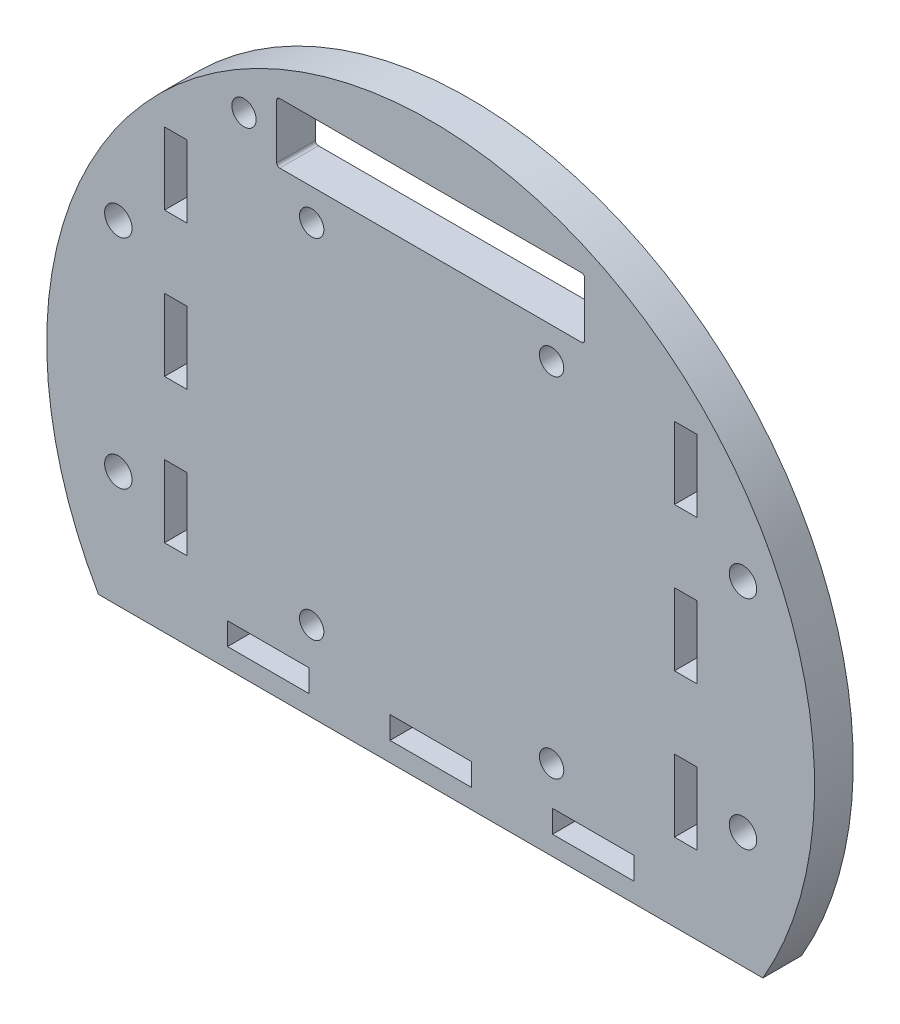
SolidWorks part; units mm, degrees
material "ABS"
ref_plane "Front Plane" through (0, 0, 0) normal (0, 0, 1) x (1, 0, 0)
ref_plane "Top Plane" through (0, 0, 0) normal (0, 1, 0) x (1, 0, 0)
ref_plane "Right Plane" through (0, 0, 0) normal (1, 0, 0) x (0, 0, -1)
sketch "Sketch1" plane through (0, 0, 0) normal (0, 0, 1) x (1, 0, 0)
  line L0 (-54.5148, -31.5775) -> (54.5148, -31.5775) construction
  line L1 (-54.5148, -31.5775) -> (54.5148, -31.5775)
  line L4 (20, -28.4025) -> (33.3333, -28.4025)
  line L5 (20, -24.7275) -> (20, -28.4025)
  line L6 (33.3333, -24.7275) -> (20, -24.7275)
  line L7 (33.3333, -28.4025) -> (33.3333, -24.7275)
  line L8 (20, -28.4025) -> (33.3333, -28.4025)
  line L9 (20, -24.7275) -> (20, -28.4025)
  line L10 (33.3333, -24.7275) -> (20, -24.7275)
  line L11 (33.3333, -28.4025) -> (33.3333, -24.7275)
  line L12 (-6.6667, -28.4025) -> (6.6667, -28.4025)
  line L13 (-6.6667, -24.7275) -> (-6.6667, -28.4025)
  line L14 (6.6667, -24.7275) -> (-6.6667, -24.7275)
  line L15 (6.6667, -28.4025) -> (6.6667, -24.7275)
  line L16 (-6.6667, -28.4025) -> (6.6667, -28.4025)
  line L17 (-6.6667, -24.7275) -> (-6.6667, -28.4025)
  line L18 (6.6667, -24.7275) -> (-6.6667, -24.7275)
  line L19 (6.6667, -28.4025) -> (6.6667, -24.7275)
  line L20 (-33.3333, -28.4025) -> (-20, -28.4025)
  line L21 (-33.3333, -24.7275) -> (-33.3333, -28.4025)
  line L22 (-20, -24.7275) -> (-33.3333, -24.7275)
  line L23 (-20, -28.4025) -> (-20, -24.7275)
  line L24 (-33.3333, -28.4025) -> (-20, -28.4025)
  line L25 (-33.3333, -24.7275) -> (-33.3333, -28.4025)
  line L26 (-20, -24.7275) -> (-33.3333, -24.7275)
  line L27 (-20, -28.4025) -> (-20, -24.7275)
  line L28 (-43.675, -18.8184) -> (-40, -18.8184)
  line L29 (-43.675, -7.0002) -> (-43.675, -18.8184)
  line L30 (-40, -7.0002) -> (-43.675, -7.0002)
  line L31 (-40, -18.8184) -> (-40, -7.0002)
  line L32 (-43.675, -18.8184) -> (-40, -18.8184)
  line L33 (-43.675, -7.0002) -> (-43.675, -18.8184)
  line L34 (-40, -7.0002) -> (-43.675, -7.0002)
  line L35 (-40, -18.8184) -> (-40, -7.0002)
  line L36 (-40, 16.6362) -> (-43.675, 16.6362)
  line L37 (-40, 4.818) -> (-40, 16.6362)
  line L38 (-43.675, 4.818) -> (-40, 4.818)
  line L39 (-43.675, 16.6362) -> (-43.675, 4.818)
  line L40 (-40, 16.6362) -> (-43.675, 16.6362)
  line L41 (-40, 4.818) -> (-40, 16.6362)
  line L42 (-43.675, 4.818) -> (-40, 4.818)
  line L43 (-43.675, 16.6362) -> (-43.675, 4.818)
  line L44 (-40, 40.2725) -> (-43.675, 40.2725)
  line L45 (-40, 28.4544) -> (-40, 40.2725)
  line L46 (-43.675, 28.4544) -> (-40, 28.4544)
  line L47 (-43.675, 40.2725) -> (-43.675, 28.4544)
  line L48 (-40, 40.2725) -> (-43.675, 40.2725)
  line L49 (-40, 28.4544) -> (-40, 40.2725)
  line L50 (-43.675, 28.4544) -> (-40, 28.4544)
  line L51 (-43.675, 40.2725) -> (-43.675, 28.4544)
  line L52 (43.675, -7.0002) -> (40, -7.0002)
  line L53 (43.675, -18.8184) -> (43.675, -7.0002)
  line L54 (40, -18.8184) -> (43.675, -18.8184)
  line L55 (40, -7.0002) -> (40, -18.8184)
  line L56 (43.675, -7.0002) -> (40, -7.0002)
  line L57 (43.675, -18.8184) -> (43.675, -7.0002)
  line L58 (40, -18.8184) -> (43.675, -18.8184)
  line L59 (40, -7.0002) -> (40, -18.8184)
  line L60 (40, 4.818) -> (43.675, 4.818)
  line L61 (40, 16.6362) -> (40, 4.818)
  line L62 (43.675, 16.6362) -> (40, 16.6362)
  line L63 (43.675, 4.818) -> (43.675, 16.6362)
  line L64 (40, 4.818) -> (43.675, 4.818)
  line L65 (40, 16.6362) -> (40, 4.818)
  line L66 (43.675, 16.6362) -> (40, 16.6362)
  line L67 (43.675, 4.818) -> (43.675, 16.6362)
  line L68 (40, 28.4544) -> (43.675, 28.4544)
  line L69 (40, 40.2725) -> (40, 28.4544)
  line L70 (43.675, 40.2725) -> (40, 40.2725)
  line L71 (43.675, 28.4544) -> (43.675, 40.2725)
  line L72 (40, 28.4544) -> (43.675, 28.4544)
  line L73 (40, 40.2725) -> (40, 28.4544)
  line L74 (43.675, 40.2725) -> (40, 40.2725)
  line L75 (43.675, 28.4544) -> (43.675, 40.2725)
  line L76 (25.265, 44.3786) -> (25.265, 53.2686)
  line L77 (-24.765, 43.8786) -> (24.765, 43.8786)
  line L78 (-25.265, 53.2686) -> (-25.265, 44.3786)
  line L79 (24.765, 53.7686) -> (-24.765, 53.7686)
  line L80 (25.265, 44.3786) -> (25.265, 53.2686)
  line L81 (-24.765, 43.8786) -> (24.765, 43.8786)
  line L82 (-25.265, 53.2686) -> (-25.265, 44.3786)
  line L83 (24.765, 53.7686) -> (-24.765, 53.7686)
  arc A0 (54.5148, -31.5775) -> (-54.5148, -31.5775) centre (0, 0) ccw construction
  circle A1 centre (-51.25, 23.184) radius 2.25
  circle A2 centre (-51.25, 23.184) radius 2.25
  circle A3 centre (19.8443, 38.7286) radius 1.65 construction
  circle A5 centre (-51.25, -12.4964) radius 2.25
  circle A6 centre (-51.25, -12.4964) radius 2.25
  circle A7 centre (-30.6292, 48.8236) radius 2
  circle A8 centre (-30.6292, 48.8236) radius 2
  circle A9 centre (51.25, 23.184) radius 2.25
  circle A10 centre (51.25, 23.184) radius 2.25
  circle A11 centre (19.8443, -18.4214) radius 1.65 construction
  circle A13 centre (51.25, -12.4964) radius 2.25
  circle A14 centre (51.25, -12.4964) radius 2.25
  circle A15 centre (-19.5257, -18.4214) radius 1.65 construction
  arc A17 (54.5148, -31.5775) -> (-54.5148, -31.5775) centre (0, 0) ccw
  circle A18 centre (-19.5257, 38.7286) radius 1.65 construction
  circle A19 centre (19.8443, 38.7286) radius 1.65 construction
  arc A20 (24.765, 43.8786) -> (25.265, 44.3786) centre (24.765, 44.3786) ccw
  arc A21 (-25.265, 44.3786) -> (-24.765, 43.8786) centre (-24.765, 44.3786) ccw
  arc A22 (-24.765, 53.7686) -> (-25.265, 53.2686) centre (-24.765, 53.2686) ccw
  arc A23 (25.265, 53.2686) -> (24.765, 53.7686) centre (24.765, 53.2686) ccw
  arc A24 (24.765, 43.8786) -> (25.265, 44.3786) centre (24.765, 44.3786) ccw
  arc A25 (-25.265, 44.3786) -> (-24.765, 43.8786) centre (-24.765, 44.3786) ccw
  arc A26 (-24.765, 53.7686) -> (-25.265, 53.2686) centre (-24.765, 53.2686) ccw
  arc A27 (25.265, 53.2686) -> (24.765, 53.7686) centre (24.765, 53.2686) ccw
  circle A28 centre (19.8443, -18.4214) radius 1.65 construction
  circle A29 centre (-19.5257, -18.4214) radius 1.65 construction
  circle A30 centre (-19.5257, 38.7286) radius 1.65 construction
  circle A31 centre (-19.5257, 38.7286) radius 2
  circle A32 centre (-19.5257, -18.4214) radius 2
  circle A33 centre (19.8443, -18.4214) radius 2
  circle A34 centre (19.8443, 38.7286) radius 2
  dimension "D1" = 0
  dimension "D2" = 0
  dimension "D3" = 0
  dimension "D4" = 0
  dimension "D6" = 0
  dimension "D7" = 0
  dimension "D8" = 0
  dimension "D9" = 0
  dimension "D10" = 0
  dimension "D11" = 0
  dimension "D13" = 0
  dimension "D14" = 0
  dimension "D15" = 0
  dimension "D16" = 0
  dimension "D18" = 0
extrude "Boss-Extrude1" add sketch "Sketch1" against normal blind 6.35
